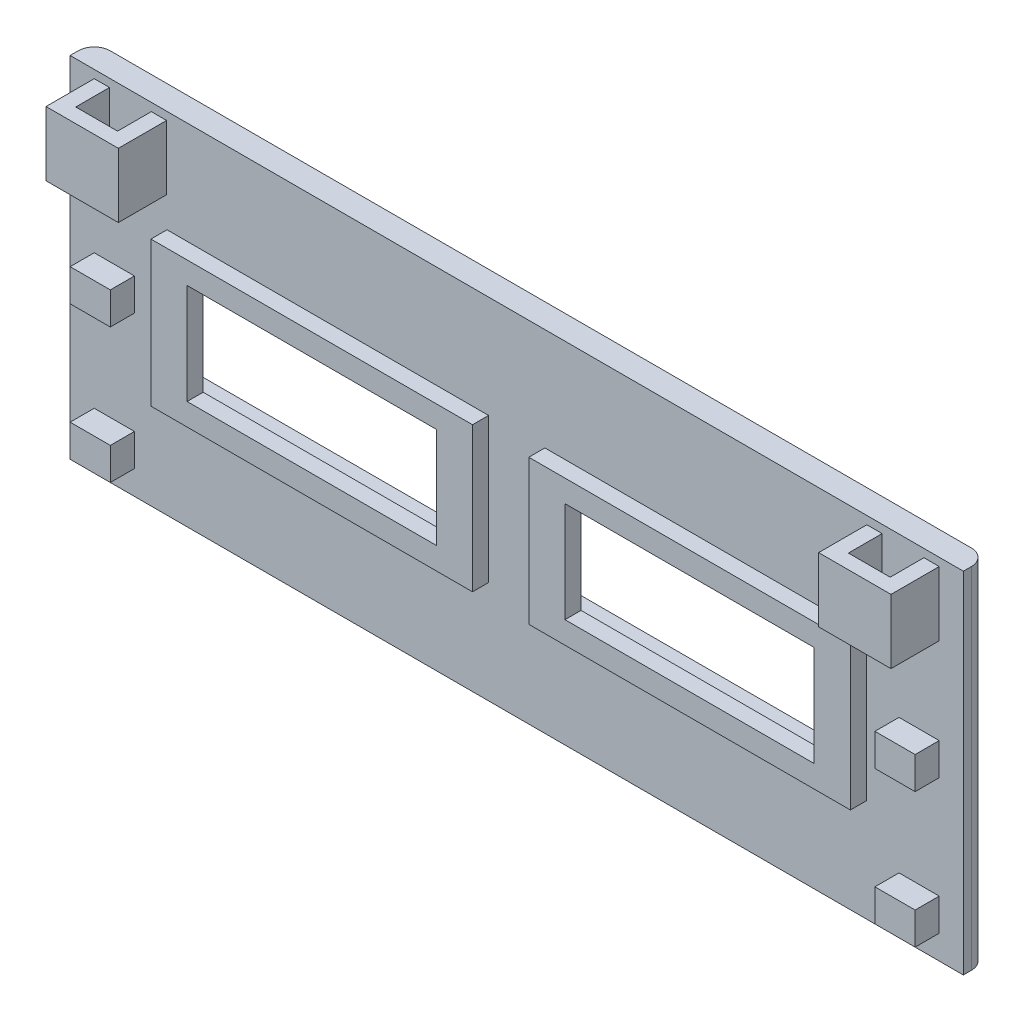
SolidWorks part; units mm, degrees
ref_plane "Front Plane" through (0, 0, 0) normal (0, 0, 1) x (1, 0, 0)
ref_plane "Top Plane" through (0, 0, 0) normal (0, 1, 0) x (1, 0, 0)
ref_plane "Right Plane" through (0, 0, 0) normal (1, 0, 0) x (0, 0, -1)
sketch "Sketch1" plane through (0, 0, 0) normal (0, 1, 0) x (1, 0, 0)
  line L1 (55.55, -25.65) -> (-55.55, -25.65)
  line L2 (55.55, -25.65) -> (55.55, 25.65)
  line L3 (55.55, 25.65) -> (-55.55, 25.65)
  line L4 (-55.55, -25.65) -> (-55.55, 25.65)
  line L5 (55.55, -25.65) -> (-55.55, 25.65) construction
  line L6 (55.55, 25.65) -> (-55.55, -25.65) construction
  point P0 (0, 0)
  dimension "D1" = 111.1
  dimension "D2" = 51.3
extrude "Boss-Extrude1" add sketch "Sketch1" along normal blind 3
sketch "Sketch2" plane through (0, 3, 0) normal (0, 1, 0) x (1, 0, 0)
  line L1 (52.65, -22.65) -> (-52.65, -22.65)
  line L2 (52.65, -22.65) -> (52.65, 22.65)
  line L3 (52.65, 22.65) -> (-52.65, 22.65)
  line L4 (-52.65, -22.65) -> (-52.65, 22.65)
  line L5 (52.65, -22.65) -> (-52.65, 22.65) construction
  line L6 (52.65, 22.65) -> (-52.65, -22.65) construction
  line L7 (55.55, 25.65) -> (-55.55, 25.65)
  line L8 (55.55, 25.65) -> (55.55, -25.65)
  line L9 (55.55, -25.65) -> (-55.55, -25.65)
  line L10 (-55.55, 25.65) -> (-55.55, -25.65)
  line L11 (55.55, 25.65) -> (-55.55, -25.65) construction
  line L12 (55.55, -25.65) -> (-55.55, 25.65) construction
  point P0 (0, 0)
  point P6 (0, 0)
  dimension "D1" = 105.3
  dimension "D2" = 45.3
extrude "Boss-Extrude2" add sketch "Sketch2" along normal blind 40.5
sketch "Sketch5" plane through (0, 0, -25.65) normal (0, 0, -1) x (-1, 0, 0)
  line L0 (0, 43.5) -> (0, 0) construction
  line L1 (-55.55, 43.5) -> (55.55, 43.5) construction
  line L2 (-55.55, 43.5) -> (0, 43.5) construction
  line L3 (-27.775, 43.5) -> (-27.775, 0) construction
  line L4 (-55.55, 0) -> (55.55, 0) construction
  line L5 (42, 29.4) -> (5, 29.4)
  line L6 (-42, 14.1) -> (-5, 14.1)
  line L7 (-42, 14.1) -> (-42, 29.4)
  line L8 (-42, 29.4) -> (-5, 29.4)
  line L9 (-5, 14.1) -> (-5, 29.4)
  line L10 (-42, 14.1) -> (-5, 29.4) construction
  line L11 (-42, 29.4) -> (-5, 14.1) construction
  line L12 (5, 14.1) -> (5, 29.4)
  line L13 (42, 14.1) -> (5, 14.1)
  line L14 (42, 14.1) -> (42, 29.4)
  line L15 (55.55, 21.75) -> (-55.55, 21.75) construction
  line L16 (55.55, 43.5) -> (55.55, 0) construction
  line L17 (-55.55, 43.5) -> (-55.55, 0) construction
  dimension "D1" = 10
  dimension "D2" = 15.3
  dimension "D3" = 37
sketch "Sketch10" plane through (0, 0, -22.65) normal (0, 0, 1) x (1, 0, 0)
  line L0 (0, 43.5) -> (0, 0) construction
  line L1 (-55.55, 43.5) -> (55.55, 43.5) construction
  line L3 (63.1223, -12.5986) -> (-63.1223, -12.5986)
  line L4 (63.1223, -12.5986) -> (63.1223, 56.0986)
  line L5 (63.1223, 56.0986) -> (-63.1223, 56.0986)
  line L6 (-63.1223, -12.5986) -> (-63.1223, 56.0986)
  line L7 (63.1223, -12.5986) -> (-63.1223, 56.0986) construction
  line L8 (63.1223, 56.0986) -> (-63.1223, -12.5986) construction
  point P5 (0, 21.75)
extrude "Cut-Extrude2" cut sketch "Sketch10" along normal blind 53
sketch "Sketch11" plane through (0, 0, -22.65) normal (0, 0, 1) x (1, 0, 0)
  line L4 (-55.55, 21.75) -> (55.55, 21.75) construction
  line L5 (0, 43.5) -> (0, 0) construction
  line L6 (-47.55, 19.75) -> (-52.55, 19.75)
  line L7 (-47.55, 19.75) -> (-47.55, 23.75)
  line L8 (-47.55, 23.75) -> (-52.55, 23.75)
  line L9 (-52.55, 19.75) -> (-52.55, 23.75)
  line L10 (-47.55, 19.75) -> (-52.55, 23.75) construction
  line L11 (-47.55, 23.75) -> (-52.55, 19.75) construction
  line L12 (-47.55, 3) -> (-52.55, 3)
  line L13 (-47.55, 3) -> (-47.55, 7)
  line L14 (-47.55, 7) -> (-52.55, 7)
  line L15 (-52.55, 3) -> (-52.55, 7)
  line L16 (-47.55, 3) -> (-52.55, 7) construction
  line L17 (-47.55, 7) -> (-52.55, 3) construction
  line L18 (52.55, 3) -> (52.55, 7)
  line L19 (47.55, 3) -> (52.55, 3)
  line L20 (47.55, 3) -> (47.55, 7)
  line L21 (47.55, 7) -> (52.55, 7)
  line L22 (47.55, 19.75) -> (47.55, 23.75)
  line L23 (47.55, 19.75) -> (52.55, 19.75)
  line L24 (52.55, 19.75) -> (52.55, 23.75)
  line L25 (47.55, 23.75) -> (52.55, 23.75)
  line L26 (-55.55, 0) -> (55.55, 0) construction
  line L27 (-55.55, 43.5) -> (-55.55, 0) construction
  point P10 (-50.05, 21.75)
  point P15 (-50.05, 5)
  dimension "D1" = 4
  dimension "D2" = 5
  dimension "D3" = 3
  dimension "D4" = 3
  dimension "D5" = 3
  dimension "D6" = 21.75
extrude "Boss-Extrude7" add sketch "Sketch11" along normal blind 3
sketch "Sketch12" plane through (0, 0, -22.65) normal (0, 0, 1) x (1, 0, 0)
  line L0 (0, 43.5) -> (0, 0) construction
  line L1 (55.55, 43.5) -> (-55.55, 43.5) construction
  line L3 (-52.55, 42.5) -> (-43.55, 42.5)
  line L4 (-52.55, 42.5) -> (-52.55, 34.5)
  line L5 (-52.55, 34.5) -> (-43.55, 34.5)
  line L6 (-43.55, 42.5) -> (-43.55, 34.5)
  line L7 (-52.55, 42.5) -> (-43.55, 34.5) construction
  line L8 (-52.55, 34.5) -> (-43.55, 42.5) construction
  line L9 (-55.55, 43.5) -> (-55.55, 0) construction
  line L10 (52.55, 42.5) -> (43.55, 42.5)
  line L11 (43.55, 42.5) -> (43.55, 34.5)
  line L12 (52.55, 34.5) -> (43.55, 34.5)
  line L13 (52.55, 42.5) -> (52.55, 34.5)
  point P5 (-48.05, 38.5)
  point P10 (-48.05, 42.5)
  dimension "D1" = 9
  dimension "D2" = 8
  dimension "D3" = 1
  dimension "D4" = 3
extrude "Boss-Extrude8" add sketch "Sketch12" along normal blind 6
sketch "Sketch13" plane through (0, 42.5, 0) normal (0, 1, 0) x (1, 0, 0)
  line L0 (-50.65, 22.65) -> (-45.45, 22.65)
  line L1 (55.55, 22.65) -> (-55.55, 22.65) construction
  line L2 (-43.55, 22.65) -> (-52.55, 22.65) construction
  line L3 (-45.45, 22.65) -> (-45.45, 18.45)
  line L4 (-45.45, 18.45) -> (-50.65, 18.45)
  line L5 (-50.65, 18.45) -> (-50.65, 22.65)
  line L6 (-48.05, 16.65) -> (-48.05, 22.65) construction
  line L7 (-43.55, 16.65) -> (-52.55, 16.65) construction
  line L8 (0, 25.65) -> (0, 22.65) construction
  line L9 (55.55, 25.65) -> (-55.55, 25.65) construction
  line L10 (50.65, 22.65) -> (45.45, 22.65)
  line L11 (50.65, 18.45) -> (50.65, 22.65)
  line L12 (45.45, 18.45) -> (50.65, 18.45)
  line L13 (45.45, 22.65) -> (45.45, 18.45)
  point P12 (-48.05, 22.65)
  dimension "D1" = 5.2
  dimension "D2" = 4.2
extrude "Cut-Extrude3" cut sketch "Sketch13" against normal blind 12
fillet "Fillet2" radius 2 2 edges at (55.55, 21.75, -25.65) (-55.55, 21.75, -25.65)
extrude "Cut-Extrude5" cut sketch "Sketch5" against normal blind 3 contours L7 L6 L9 L8 | L5 L12 L13 L14
sketch "Sketch15" plane through (0, 0, -22.65) normal (0, 0, 1) x (1, 0, 0)
  line L0 (-23.5, 29.4) -> (-23.5, 14.1) construction
  line L1 (-42, 29.4) -> (-5, 29.4) construction
  line L2 (-42, 14.1) -> (-5, 14.1) construction
  line L3 (0, 43.5) -> (0, 0) construction
  line L4 (55.55, 43.5) -> (-55.55, 43.5) construction
  line L5 (39, 15.5) -> (8, 15.5)
  line L6 (-39, 28) -> (-8, 28)
  line L7 (-39, 28) -> (-39, 15.5)
  line L8 (-39, 15.5) -> (-8, 15.5)
  line L9 (-8, 28) -> (-8, 15.5)
  line L10 (-39, 28) -> (-8, 15.5) construction
  line L11 (-39, 15.5) -> (-8, 28) construction
  line L12 (8, 28) -> (8, 15.5)
  line L13 (39, 28) -> (8, 28)
  line L14 (39, 28) -> (39, 15.5)
  line L15 (43.5, 12.75) -> (3.5, 12.75)
  line L16 (-43.5, 30.75) -> (-3.5, 30.75)
  line L17 (-43.5, 30.75) -> (-43.5, 12.75)
  line L18 (-43.5, 12.75) -> (-3.5, 12.75)
  line L19 (-3.5, 30.75) -> (-3.5, 12.75)
  line L20 (-43.5, 30.75) -> (-3.5, 12.75) construction
  line L21 (-43.5, 12.75) -> (-3.5, 30.75) construction
  line L22 (3.5, 30.75) -> (3.5, 12.75)
  line L23 (43.5, 30.75) -> (3.5, 30.75)
  line L24 (43.5, 30.75) -> (43.5, 12.75)
  point P11 (-23.5, 21.75)
  point P20 (-23.5, 21.75)
  dimension "D1" = 31
  dimension "D2" = 12.5
  dimension "D3" = 40
  dimension "D4" = 18
extrude "Boss-Extrude9" add sketch "Sketch15" along normal blind 2
